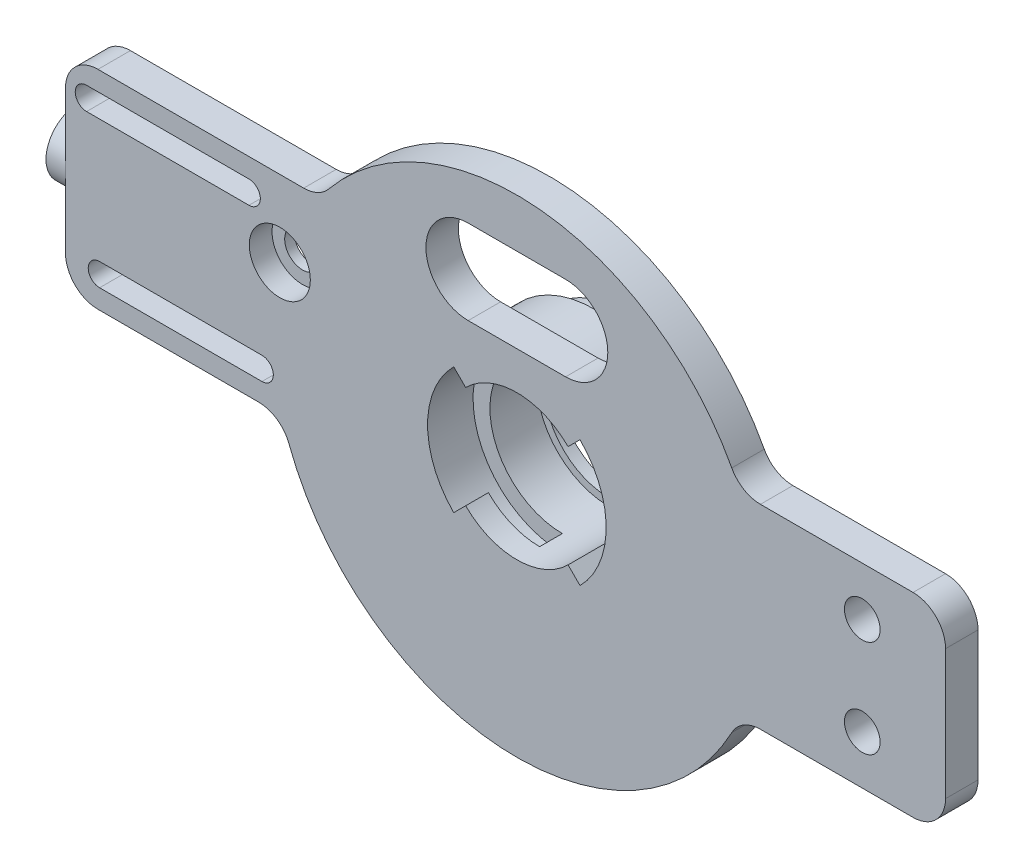
SolidWorks part; units mm, degrees
ref_plane "Front Plane" through (0, 0, 0) normal (0, 0, 1) x (1, 0, 0)
ref_plane "Top Plane" through (0, 0, 0) normal (0, 1, 0) x (1, 0, 0)
ref_plane "Right Plane" through (0, 0, 0) normal (1, 0, 0) x (0, 0, -1)
ref_plane "Plane1" through (0, 0, -8.5) normal (0, 0, -1) x (-1, 0, 0)
sketch "Sketch2" plane through (0, 0, -8.5) normal (0, 0, -1) x (-1, 0, 0)
  line L2 (31, 34.5) -> (16, 34.5)
  line L3 (16, 27.5) -> (31, 27.5)
  line L4 (31, 37.5) -> (16, 37.5)
  line L5 (16, 24.5) -> (31, 24.5)
  circle A0 centre (23.5, 7.5) radius 37.5
  circle A1 centre (23.5, 7.5) radius 4.2 construction
  circle A2 centre (23.5, 7.5) radius 4.2
  arc A5 (16, 34.5) -> (16, 27.5) centre (16, 31) ccw
  arc A6 (31, 27.5) -> (31, 34.5) centre (31, 31) ccw
  arc A7 (16, 37.5) -> (16, 24.5) centre (16, 31) ccw
  arc A8 (31, 24.5) -> (31, 37.5) centre (31, 31) ccw
  dimension "D1" = 75
  dimension "D2" = 3
extrude "Boss-Extrude1" add sketch "Sketch2" along normal blind 5 contours A0 A8 L5 A7 L4 A2
sketch "Sketch3" plane through (0, 0, -8.5) normal (0, 0, 1) x (1, 0, 0)
  circle A0 centre (-23.5, 7.5) radius 11.15
  dimension "D1" = 22.3
extrude "Cut-Extrude1" cut sketch "Sketch3" against normal through all
sketch "Sketch5" plane through (0, 0, -13.5) normal (0, 0, -1) x (-1, 0, 0)
  circle A0 centre (23.5, 7.5) radius 11.15 construction
  circle A1 centre (23.5, 7.5) radius 11.15
  circle A2 centre (23.5, 7.5) radius 14.15
  dimension "D1" = 3
extrude "Boss-Extrude2" add sketch "Sketch5" along normal blind 10
sketch "Sketch6" plane through (0, 0, -23.5) normal (0, 0, -1) x (-1, 0, 0)
  circle A1 centre (23.5, 7.5) radius 14.15
  circle A2 centre (23.5, 7.5) radius 14.15
  circle A3 centre (23.5, 7.5) radius 9
  dimension "D2" = 18
  dimension "D1" = 0
extrude "Boss-Extrude3" add sketch "Sketch6" against normal blind 2
sketch "Sketch7" plane through (0, 0, -21.5) normal (0, 0, 1) x (1, 0, 0)
  circle A1 centre (-23.5, 7.5) radius 11.15
  circle A2 centre (-23.5, 7.5) radius 11.15
  dimension "D1" = 0
extrude "Cut-Extrude2" cut sketch "Sketch7" against normal blind 10
sketch "Sketch8" plane through (0, 0, -22.5) normal (0, 0, -1) x (-1, 0, 0)
  circle A0 centre (23.5, 7.5) radius 14.15
  circle A1 centre (23.5, 7.5) radius 10
  dimension "D1" = 20
extrude "Boss-Extrude4" add sketch "Sketch8" along normal blind 2
sketch "Sketch9" plane through (0, 0, -8.5) normal (0, 0, 1) x (1, 0, 0)
  line L0 (7.5, 22.5) -> (17.5, 22.5)
  line L1 (17.5, 22.5) -> (17.5, -7.5)
  line L2 (7.5, -7.5) -> (17.5, -7.5)
  line L3 (7.5, 22.5) -> (7.5, -7.5)
  circle A0 centre (-23.5, 7.5) radius 35
  circle M7 centre (-23.5, 7.5) radius 37.5
  dimension "D1" = 70
  dimension "D2" = 10
extrude "Boss-Extrude5" add sketch "Sketch9" along normal blind 5 and the other way blind 5 contours L2 L1 L0 M7 | A0 L2 L0 M7
sketch "Sketch10" plane through (17.5, 0, 0) normal (1, 0, 0) x (0, 0, -1)
  line L4 (13.5, 22.5) -> (3.5, 22.5)
  line L5 (3.5, 22.5) -> (3.5, -7.5)
  line L6 (3.5, -7.5) -> (13.5, -7.5)
  line L7 (13.5, -7.5) -> (13.5, 22.5)
  line L8 (13.5, 22.5) -> (3.5, 22.5)
  line L9 (3.5, 22.5) -> (3.5, -7.5)
  line L10 (3.5, -7.5) -> (13.5, -7.5)
  line L11 (13.5, -7.5) -> (13.5, 22.5)
  dimension "D1" = 0
extrude "Boss-Extrude6" add sketch "Sketch10" along normal blind 10
sketch "Sketch11" plane through (0, 0, -3.5) normal (0, 0, 1) x (1, 0, 0)
  line L3 (27.5, 22.5) -> (8.1228, 22.5)
  line L4 (8.1228, -7.5) -> (27.5, -7.5)
  line L5 (27.5, -7.5) -> (27.5, 22.5)
  line L6 (27.5, 22.5) -> (8.1228, 22.5)
  line L7 (8.1228, -7.5) -> (27.5, -7.5)
  line L8 (27.5, -7.5) -> (27.5, 22.5)
  arc A1 (8.1228, -7.5) -> (8.1228, 22.5) centre (-23.5, 7.5) ccw
  arc A2 (8.1228, -7.5) -> (8.1228, 22.5) centre (-23.5, 7.5) ccw
  dimension "D1" = 0
extrude "Cut-Extrude3" cut sketch "Sketch11" against normal up to surface (5 mm away) up to face at (-23.5, 31, -8.5)
sketch "Sketch12" plane through (0, 0, -8.5) normal (0, 0, 1) x (1, 0, 0)
  circle A0 centre (17.5, 15) radius 2.75
  circle A1 centre (17.5, 0) radius 2.75
extrude "Cut-Extrude4" cut sketch "Sketch12" against normal through all
sketch "Sketch13" plane through (0, 0, -13.5) normal (0, 0, -1) x (-1, 0, 0)
  line L0 (-21.0218, -6.1) -> (-13.9782, -6.1)
  line L1 (-22.2343, 0) -> (-19.8671, -4.1)
  line L2 (-19.8671, -4.1) -> (-15.1329, -4.1)
  line L3 (-15.1329, -4.1) -> (-12.7657, 0)
  line L4 (-12.7657, 0) -> (-15.1329, 4.1)
  line L5 (-15.1329, 4.1) -> (-19.8671, 4.1)
  line L6 (-19.8671, 4.1) -> (-22.2343, 0)
  line L7 (-22.2343, 15) -> (-19.8671, 10.9)
  line L8 (-19.8671, 10.9) -> (-15.1329, 10.9)
  line L9 (-15.1329, 10.9) -> (-12.7657, 15)
  line L10 (-12.7657, 15) -> (-15.1329, 19.1)
  line L11 (-15.1329, 19.1) -> (-19.8671, 19.1)
  line L12 (-19.8671, 19.1) -> (-22.2343, 15)
  line L13 (-13.9782, -6.1) -> (-10.4563, 0)
  line L14 (-10.4563, 0) -> (-13.9782, 6.1)
  line L15 (-13.9782, 6.1) -> (-21.0218, 6.1)
  line L16 (-21.0218, 6.1) -> (-24.5437, 0)
  line L17 (-24.5437, 0) -> (-21.0218, -6.1)
  line L18 (-21.0218, 8.9) -> (-13.9782, 8.9)
  line L19 (-13.9782, 8.9) -> (-10.4563, 15)
  line L20 (-10.4563, 15) -> (-13.9782, 21.1)
  line L21 (-13.9782, 21.1) -> (-21.0218, 21.1)
  line L22 (-21.0218, 21.1) -> (-24.5437, 15)
  line L23 (-24.5437, 15) -> (-21.0218, 8.9)
  circle A0 centre (-17.5, 0) radius 4.1 construction
  circle A1 centre (-17.5, 15) radius 4.1 construction
  dimension "D1" = 8.2
  dimension "D2" = 8.2
  dimension "D3" = 2
extrude "Boss-Extrude7" add sketch "Sketch13" along normal blind 5
sketch "Sketch15" plane through (0, 0, -8.5) normal (0, 0, 1) x (1, 0, 0)
  circle A0 centre (-23.5, 7.5) radius 13.75
  dimension "D1" = 27.5
extrude "Cut-Extrude5" cut sketch "Sketch15" against normal blind 7
sketch "Sketch17" plane through (0, 0, -13.5) normal (0, 0, -1) x (-1, 0, 0)
  circle A0 centre (23.5, 7.5) radius 16.25
  circle A1 centre (23.5, 7.5) radius 14.15
  dimension "D1" = 32.5
extrude "Boss-Extrude8" add sketch "Sketch17" along normal blind 7
sketch "Sketch18" plane through (0, 0, -15.5) normal (0, 0, 1) x (1, 0, 0)
  line L0 (-23.5, 7.5) -> (-23.5, 21.25)
  line L1 (-23.5, 7.5) -> (-13.7773, 17.2227)
  line L2 (-23.5, 7.5) -> (-33.2227, 17.2227)
  line L3 (-23.5, 7.5) -> (-33.2227, -2.2227)
  line L4 (-23.5, 7.5) -> (-13.7773, -2.2227)
  circle A0 centre (-23.5, 7.5) radius 11.15
  circle A1 centre (-23.5, 7.5) radius 13.75
  circle M8 centre (-23.5, 7.5) radius 13.75
  circle M9 centre (-23.5, 7.5) radius 11.15
  dimension "D1" = 45
  dimension "D2" = 45
  dimension "D3" = 90
  dimension "D4" = 90
extrude "Boss-Extrude9" add sketch "Sketch18" along normal blind 7 contours L2 L0 M9 M8 | L1 L0 M9 M8 | L4 L3 M9 M8
sketch "Sketch19" plane through (0, 0, -15.5) normal (0, 0, 1) x (1, 0, 0)
  line L0 (-23.5, 7.5) -> (-23.5, 21.25)
  line L1 (-23.5, 21.25) -> (-23.5, -6.25)
  line L2 (-23.5, 7.5) -> (-9.75, 7.5)
  line L3 (-9.75, 7.5) -> (-37.25, 7.5)
  line L4 (-15.6158, 15.3842) -> (-13.7773, 17.2227)
  line L5 (-33.2227, 17.2227) -> (-31.3842, 15.3842)
  line L6 (-31.3842, -0.3842) -> (-33.2227, -2.2227)
  line L7 (-15.6158, -0.3842) -> (-13.7773, -2.2227)
  circle A0 centre (-23.5, 7.5) radius 13.75
  circle A1 centre (-23.5, 7.5) radius 11.15
  line M5 (-13.7773, 17.2227) -> (-15.6158, 15.3842)
extrude "Cut-Extrude7" cut sketch "Sketch19" along normal blind 3.5 contours A1 A0 L1 M5 | A1 L6 A0 L1
sketch "Sketch20" plane through (0, 0, -22.5) normal (0, 0, 1) x (1, 0, 0)
  circle A1 centre (-23.5, 7.5) radius 11.15
  circle A2 centre (-23.5, 7.5) radius 11.15
  dimension "D1" = 0
extrude "Cut-Extrude8" cut sketch "Sketch20" against normal blind 0.2
sketch "Sketch21" plane through (0, 0, -8.5) normal (0, 0, 1) x (1, 0, 0)
  line L0 (-61, 7.5) -> (-76, 7.5)
  line L1 (-61, 17.5) -> (-76, 17.5)
  line L2 (-61, -2.5) -> (-76, -2.5)
  line L3 (-61, 17.5) -> (-57.1211, 17.5)
  line L4 (-57.1211, 17.5) -> (-57.1211, -2.5)
  line L5 (-57.1211, -2.5) -> (-61, -2.5)
  line L6 (-76, -2.5) -> (-76, 17.5)
  arc A0 (10.8693, 22.5) -> (10.8693, -7.5) centre (-23.5, 7.5) ccw construction
  arc M22 (10.8693, 22.5) -> (10.8693, -7.5) centre (-23.5, 7.5) ccw
  dimension "D1" = 15
  dimension "D2" = 10
  dimension "D3" = 10
extrude "Boss-Extrude10" add sketch "Sketch21" against normal up to surface (5 mm away) contours L6 L0 L3 L1 M22 | L6 L2 L5 L0 M22 up to face at (17.5, 15, -13.5)
sketch "Sketch22" plane through (-76, 0, 0) normal (-1, 0, 0) x (0, 0, 1)
  line L4 (-13.5, 17.5) -> (-13.5, -2.5)
  line L5 (-13.5, -2.5) -> (-8.5, -2.5)
  line L6 (-8.5, -2.5) -> (-8.5, 17.5)
  line L7 (-8.5, 17.5) -> (-13.5, 17.5)
  line L8 (-13.5, 17.5) -> (-13.5, -2.5)
  line L9 (-13.5, -2.5) -> (-8.5, -2.5)
  line L10 (-8.5, -2.5) -> (-8.5, 17.5)
  line L11 (-8.5, 17.5) -> (-13.5, 17.5)
  dimension "D1" = 0
extrude "Boss-Extrude11" add sketch "Sketch22" along normal blind 7
sketch "Sketch23" plane through (0, 17.5, 0) normal (0, 1, 0) x (1, 0, 0)
  line L4 (-59.6421, 13.5) -> (-83, 13.5)
  line L5 (-83, 13.5) -> (-83, 8.5)
  line L6 (-83, 8.5) -> (-59.6421, 8.5)
  line L7 (-59.6421, 8.5) -> (-59.6421, 13.5)
  line L8 (-59.6421, 13.5) -> (-83, 13.5)
  line L9 (-83, 13.5) -> (-83, 8.5)
  line L10 (-83, 8.5) -> (-59.6421, 8.5)
  line L11 (-59.6421, 8.5) -> (-59.6421, 13.5)
  dimension "D1" = 0
extrude "Boss-Extrude12" add sketch "Sketch23" along normal blind 12
sketch "Sketch24" plane through (-59.6421, 0, 0) normal (1, 0, 0) x (0, 0, -1)
  line L4 (8.5, 17.5) -> (13.5, 17.5)
  line L5 (13.5, 17.5) -> (13.5, 29.5)
  line L6 (13.5, 29.5) -> (8.5, 29.5)
  line L7 (8.5, 29.5) -> (8.5, 17.5)
  line L8 (8.5, 17.5) -> (13.5, 17.5)
  line L9 (13.5, 17.5) -> (13.5, 29.5)
  line L10 (13.5, 29.5) -> (8.5, 29.5)
  line L11 (8.5, 29.5) -> (8.5, 17.5)
  dimension "D1" = 0
extrude "Boss-Extrude13" add sketch "Sketch24" along normal blind 12
sketch "Sketch25" plane through (-83, 0, 0) normal (-1, 0, 0) x (0, 0, 1)
  line L4 (-8.5, -2.5) -> (-8.5, 29.5)
  line L5 (-8.5, 29.5) -> (-13.5, 29.5)
  line L6 (-13.5, 29.5) -> (-13.5, -2.5)
  line L7 (-13.5, -2.5) -> (-8.5, -2.5)
  line L8 (-8.5, -2.5) -> (-8.5, 29.5)
  line L9 (-8.5, 29.5) -> (-13.5, 29.5)
  line L10 (-13.5, 29.5) -> (-13.5, -2.5)
  line L11 (-13.5, -2.5) -> (-8.5, -2.5)
  dimension "D1" = 0
extrude "Boss-Extrude14" add sketch "Sketch25" along normal blind 10
sketch "Sketch26" plane through (0, 0, -8.5) normal (0, 0, 1) x (1, 0, 0)
  line L0 (-69.75, 24.75) -> (-89.75, 24.75)
  line L1 (-69.75, 24.75) -> (-64.75, 24.75)
  line L2 (-80.25, 2.25) -> (-87.75, 2.25)
  line L3 (-80.25, 2.25) -> (-62.75, 2.25)
  line L4 (-64.75, 24.75) -> (-89.75, 24.75) construction
  line L5 (-64.75, 23) -> (-89.75, 23)
  line L6 (-64.75, 26.5) -> (-89.75, 26.5)
  line L7 (-87.75, 2.25) -> (-62.75, 2.25) construction
  line L8 (-87.75, 4) -> (-62.75, 4)
  line L9 (-87.75, 0.5) -> (-62.75, 0.5)
  arc A0 (-64.75, 23) -> (-64.75, 26.5) centre (-64.75, 24.75) ccw
  arc A1 (-89.75, 26.5) -> (-89.75, 23) centre (-89.75, 24.75) ccw
  arc A2 (-87.75, 4) -> (-87.75, 0.5) centre (-87.75, 2.25) ccw
  arc A3 (-62.75, 0.5) -> (-62.75, 4) centre (-62.75, 2.25) ccw
  point P7 (-77.25, 24.75)
  point P13 (-75.25, 2.25)
  dimension "D1" = 5
  dimension "D2" = 20
  dimension "D3" = 3.5
  dimension "D4" = 3.5
extrude "Cut-Extrude9" cut sketch "Sketch26" against normal through all
fillet "Fillet2" radius 5 4 edges at (-53.8686, 29.5, -11) (-59.6421, -2.5, -11) (-93, -2.5, -11) (-93, 29.5, -11)
sketch "Sketch27" plane through (0, 22.5, 0) normal (0, 1, 0) x (1, 0, 0)
  line L1 (10.4563, 18.5) -> (24.5437, 18.5)
  line L2 (10.4563, 18.5) -> (10.4563, 13.5)
  line L3 (10.4563, 13.5) -> (24.5437, 13.5)
  line L4 (24.5437, 18.5) -> (24.5437, 13.5)
extrude "Cut-Extrude10" cut sketch "Sketch27" against normal through all
sketch "Sketch28" plane through (0, 0, -8.5) normal (0, 0, 1) x (1, 0, 0)
  circle A0 centre (17.5, 0) radius 2.75 construction
  circle A1 centre (17.5, 15) radius 2.75 construction
  circle A2 centre (17.5, 0) radius 2.75
  circle A3 centre (17.5, 15) radius 2.75
extrude "Boss-Extrude15" add sketch "Sketch28" against normal up to surface (5 mm away) up to face at (14.75, 0, -13.5)
sketch "Sketch29" plane through (27.5, 0, 0) normal (1, 0, 0) x (0, 0, -1)
  line L4 (8.5, 22.5) -> (8.5, -7.5)
  line L5 (8.5, -7.5) -> (13.5, -7.5)
  line L6 (13.5, -7.5) -> (13.5, 22.5)
  line L7 (13.5, 22.5) -> (8.5, 22.5)
  line L8 (8.5, 22.5) -> (8.5, -7.5)
  line L9 (8.5, -7.5) -> (13.5, -7.5)
  line L10 (13.5, -7.5) -> (13.5, 22.5)
  line L11 (13.5, 22.5) -> (8.5, 22.5)
  dimension "D1" = 0
extrude "Boss-Extrude16" add sketch "Sketch29" along normal blind 15
sketch "Sketch30" plane through (0, 0, -8.5) normal (0, 0, 1) x (1, 0, 0)
  line L0 (16.8657, 7.5) -> (42.5, 7.5)
  line L1 (42.5, 22.5) -> (42.5, -7.5) construction
  line L2 (29.6829, 0) -> (29.6829, 15)
  circle A1 centre (29.6829, 15) radius 2.75
  circle A2 centre (29.6829, 0) radius 2.75
  point P10 (29.6829, 7.5)
  dimension "D2" = 5.5
  dimension "D3" = 5.5
  dimension "D1" = 15
extrude "Cut-Extrude12" cut sketch "Sketch30" against normal blind 15
fillet "Fillet3" radius 5 4 edges at (10.8693, 22.5, -11) (42.5, 22.5, -11) (10.8693, -7.5, -11) (42.5, -7.5, -11)
sketch "Sketch33" plane through (-93, 0, 0) normal (-1, 0, 0) x (0, 0, 1)
  line L0 (-8.5, 13.5) -> (-18.5, 13.5)
  line L1 (-8.5, 2.5) -> (-8.5, 24.5) construction
  circle A0 centre (-13.5, 13.5) radius 5
  line M3 (-13.5, 24.5) -> (-13.5, 2.5)
  dimension "D1" = 10
extrude "Boss-Extrude18" add sketch "Sketch33" along normal blind 3 contours A0 L0 M3 | L0 A0 M3 | A0 L0 M3 | L0 A0 M3
sketch "Sketch34" plane through (0, 0, -8.5) normal (0, 0, 1) x (1, 0, 0)
  line L0 (-63, 24.75) -> (-60, 24.75)
  line L1 (-60, 24.75) -> (-60, 17.75)
  arc A0 (-64.75, 23) -> (-64.75, 26.5) centre (-64.75, 24.75) ccw construction
  circle A1 centre (-60, 17.75) radius 2.75
  dimension "D3" = 5.5
  dimension "D1" = 3
  dimension "D2" = 7
extrude "Cut-Extrude13" cut sketch "Sketch34" against normal through all
sketch "Sketch35" plane through (0, 0, -8.5) normal (0, 0, 1) x (1, 0, 0)
  circle A0 centre (-60, 17.75) radius 4.7
  dimension "D1" = 9.4
extrude "Cut-Extrude14" cut sketch "Sketch35" against normal blind 3.5
